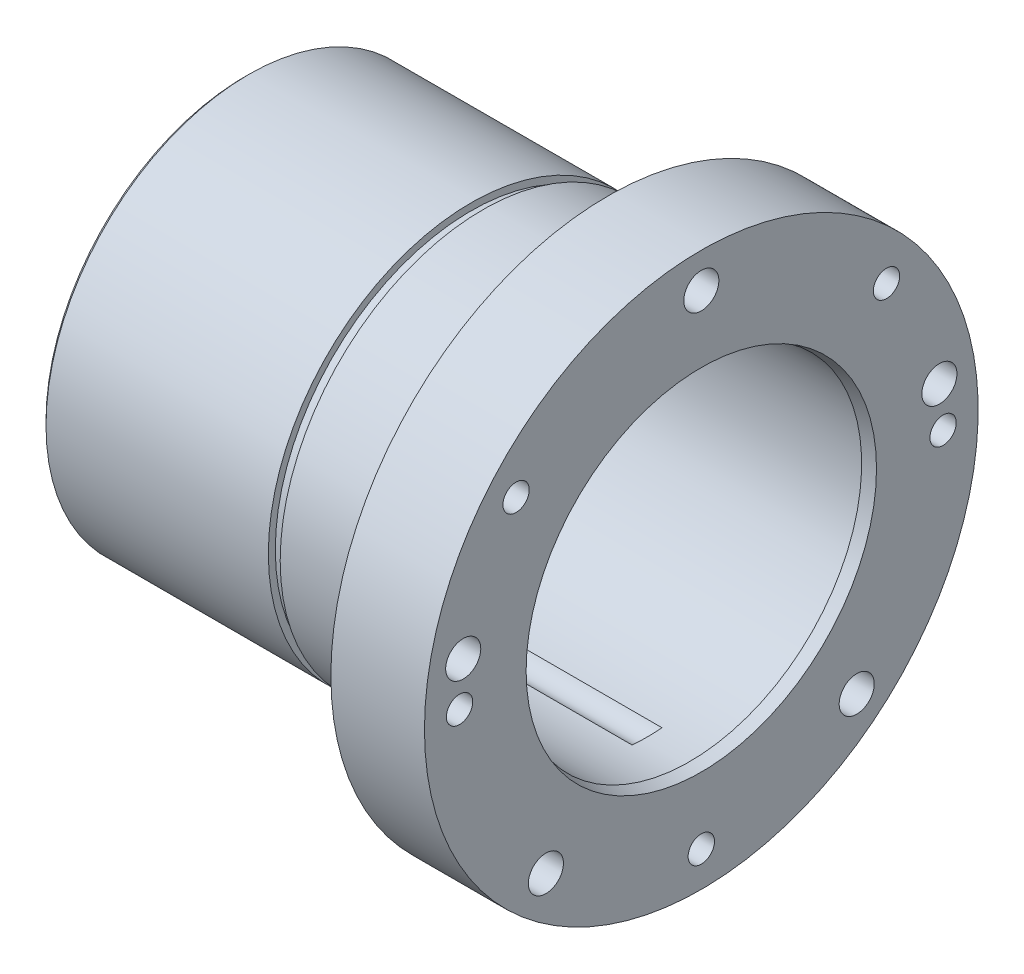
SolidWorks part; units mm, degrees
ref_plane "Front Plane" through (0, 0, 0) normal (0, 0, 1) x (1, 0, 0)
ref_plane "Top Plane" through (0, 0, 0) normal (0, 1, 0) x (1, 0, 0)
ref_plane "Right Plane" through (0, 0, 0) normal (1, 0, 0) x (0, 0, -1)
sketch "Sketch1" plane through (0, 0, 0) normal (0, 0, 1) x (1, 0, 0)
  line L0 (0, 0) -> (190.971, 0) construction
  line L1 (0, 65.0875) -> (0, 82.5424)
  line L2 (0, 82.5424) -> (92.1004, 82.5424)
  line L3 (92.1004, 82.5424) -> (92.1004, 79.7052)
  line L4 (92.1004, 79.7052) -> (96.9264, 79.7052)
  line L5 (96.9264, 79.7052) -> (96.9264, 82.5424)
  line L6 (96.9264, 82.5424) -> (147.7264, 82.5424)
  line L7 (147.7264, 82.5424) -> (147.7264, 112.7125)
  line L8 (147.7264, 112.7125) -> (185.8264, 112.7125)
  line L9 (185.8264, 112.7125) -> (185.8264, 70.0469)
  line L10 (185.8264, 70.0469) -> (19.05, 70.0468)
  line L11 (19.05, 70.0468) -> (19.05, 65.0875)
  line L12 (19.05, 65.0875) -> (0, 65.0875)
  dimension "D1" = 65.0875
  dimension "D2" = 82.5424
  dimension "D3" = 19.05
  dimension "D4" = 147.7264
  dimension "D5" = 38.1
  dimension "D6" = 70.0469
  dimension "D7" = 4.826
  dimension "D8" = 50.8
  dimension "D9" = 79.7052
  dimension "D10" = 112.7125
revolve "Revolve1" add sketch "Sketch1" angle 360 about L0
chamfer "Chamfer1" distance 1.5875 angle 45 1 edges at (0, 0, 82.5424)
chamfer "Chamfer2" distance 4.7752 angle 15 1 edges at (185.8264, 0, 70.0469)
sketch "Sketch2" plane through (0, 0, 0) normal (-1, 0, 0) x (0, 0, 1)
  line L0 (0, 0) -> (0, -73.2218) construction
  circle A0 centre (0, -66.1098) radius 7.112
  circle A1 centre (0, 0) radius 65.0875 construction
  circle A2 centre (0, 0) radius 70.0468 construction
  circle A3 centre (0, 0) radius 70.0468 construction
  point P6 (0, -65.0875)
  point P12 (0, -70.0468)
  dimension "D1" = 14.224
  dimension "D2" = 3.175
extrude "Cut-Extrude1" cut sketch "Sketch2" against normal offset from surface (163.7284 mm away) 22.098 up to face at (185.8264, 0, 71.3264)
sketch "Sketch3" plane through (147.7264, 0, 0) normal (-1, 0, 0) x (0, 0, 1)
  line L0 (0, 0) -> (0, 98.425) construction
  circle A0 centre (0, 0) radius 98.425 construction
  circle A1 centre (0, 98.425) radius 7.1437
  dimension "D1" = 196.85
  dimension "D2" = 14.2875
extrude "Cut-Extrude2" cut sketch "Sketch3" against normal through all
pattern_circular "CirPattern1" count 18 over 360 about axis through (147.7264, 0, 0) along (-1, 0, 0) skipping 1, 2, 3, 5, 6, 8, 9, 10, 12, 13, 15, 16, 17 of "Cut-Extrude2"
sketch "Sketch4" plane through (147.7264, 0, 0) normal (-1, 0, 0) x (0, 0, 1)
  line L0 (0, 0) -> (0, 98.425) construction
  circle A0 centre (0, 0) radius 98.425 construction
  circle A1 centre (0, 98.425) radius 6.35
  circle A2 centre (49.2125, 85.2386) radius 6.35
  circle A5 centre (85.2386, -49.2125) radius 6.35
  circle A6 centre (49.2125, -85.2386) radius 6.35
  circle A7 centre (0, -98.425) radius 6.35
  circle A8 centre (-49.2125, -85.2386) radius 6.35
  circle A9 centre (-85.2386, -49.2125) radius 6.35
  circle A12 centre (-49.2125, 85.2386) radius 6.35
  arc A13 (-88.2345, 43.6137) -> (-81.8878, 54.6065) centre (-85.2386, 49.2125) ccw
  arc A14 (-98.2202, 6.3467) -> (-98.2202, -6.3467) centre (-98.425, 0) ccw
  arc A15 (81.8878, 54.6065) -> (88.2345, 43.6137) centre (85.2386, 49.2125) ccw
  arc A16 (98.2202, 6.3467) -> (98.2202, -6.3467) centre (98.425, 0) ccw
  point P31 (0, 0)
  dimension "D1" = 12.7
  dimension "D2" = 12
hole_wizard "Tap Drill for 1/2-13 Tap1" positions "3DSketch1" profile "Sketch5" hole size "1/2-13" standard "ANSI Inch"
sketch3d "3DSketch1"
  point P0 (147.7264, -98.425, 0)
sketch "Sketch5" plane through (147.7264, -98.425, 0) normal (0, 1, 0) x (0, 0, 1)
  line L0 (0, 0) -> (0, 41.3195)
  line L1 (0, 41.3195) -> (5.3581, 38.1)
  line L2 (5.3581, 38.1) -> (5.3581, 0.5328)
  line L3 (5.3581, 0.5328) -> (5.9931, 0)
  line L5 (5.9931, 0) -> (0, 0)
  line L6 (-5.3581, 0.5328) -> (-5.9931, 0) construction
  line L10 (0, 41.3195) -> (-5.3581, 38.1) construction
  line L11 (0, -6.35) -> (0, 107.95) construction
  dimension "Hole Dia." = 10.7163
  dimension "Hole Depth" = 38.1
  dimension "Near C'Sink Dia." = 11.9863
  dimension "Near C'Sink Angle" = 100
  dimension "Drill Angle" = 118
pattern_circular "CirPattern2" count 36 over 360 about axis through (147.7264, 0, 0) along (-1, 0, 0) skipping 1, 2, 3, 4, 5, 6, 7, 8, 10, 11, 12, 14, 15, 16, 17, 18, 19, 20, 21, 22, 24, 25, 26, 28, 29, 30, 31, 32, 33, 34, 35 of "Tap Drill for 1/2-13 Tap1"
